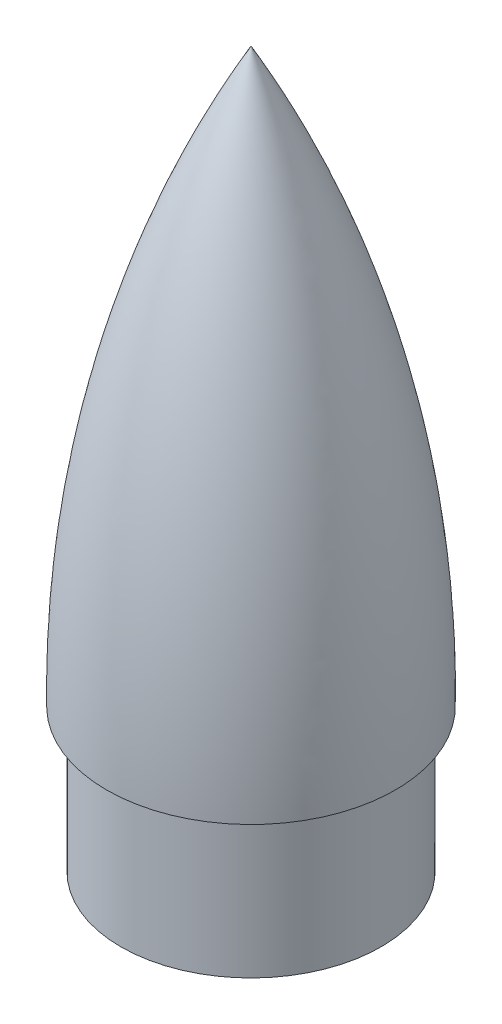
SolidWorks part; units mm, degrees
material "ABS"
ref_plane "Спереди" through (0, 0, 0) normal (0, 0, 1) x (1, 0, 0)
ref_plane "Сверху" through (0, 0, 0) normal (0, 1, 0) x (1, 0, 0)
ref_plane "Справа" through (0, 0, 0) normal (1, 0, 0) x (0, 0, -1)
sketch "Эскиз1" plane through (0, 0, 0) normal (0, 0, 1) x (1, 0, 0)
  line L0 (0, 100) -> (0, 0)
  line L1 (0, 0) -> (-18.2, 0)
  line L2 (-18.2, 0) -> (-18.2, 20)
  line L3 (-18.2, 20) -> (-20.2, 20)
  line L5 (0, 40.2645) -> (0, -26.3763) construction
  arc A1 (-20.2, 20) -> (0, 100) centre (139.7855, 22.1539) cw
  dimension "D5" = 160
  dimension "D1" = 40.4
  dimension "D2" = 100
  dimension "D3" = 20
  dimension "D4" = 2
revolve "Повернуть1" add sketch "Эскиз1" angle 360 about L5
